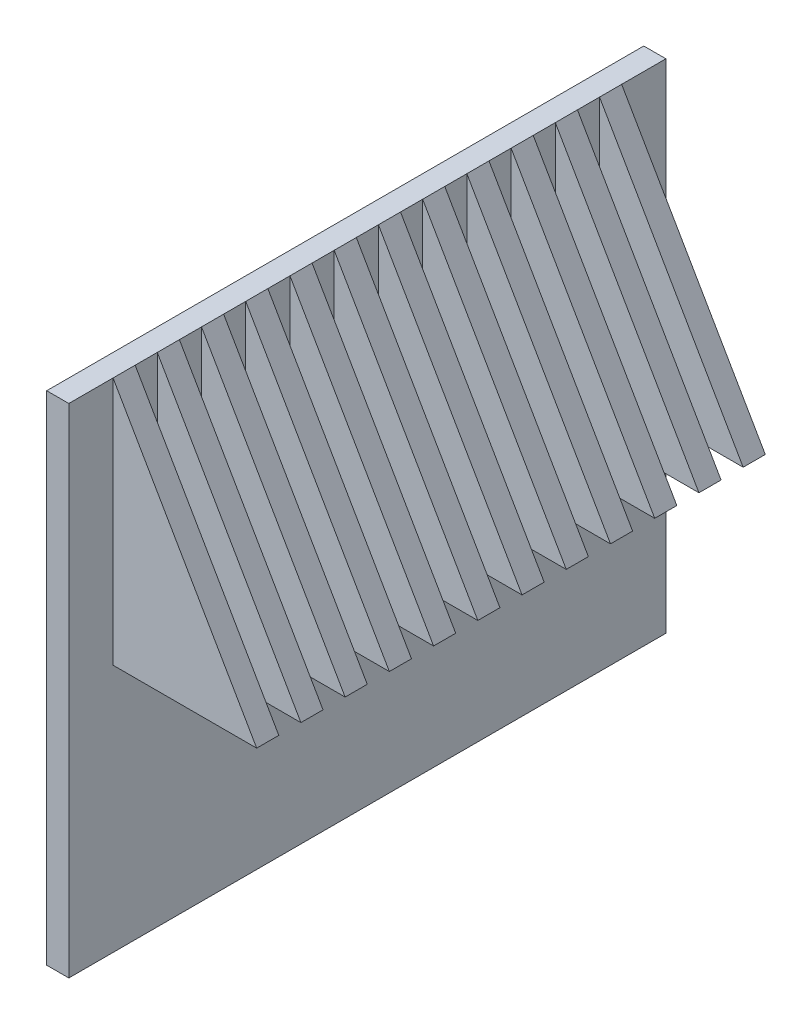
SolidWorks part; units mm, degrees
material "A286 Iron Base Superalloy"
ref_plane "Front Plane" through (0, 0, 0) normal (0, 0, 1) x (1, 0, 0)
ref_plane "Top Plane" through (0, 0, 0) normal (0, 1, 0) x (1, 0, 0)
ref_plane "Right Plane" through (0, 0, 0) normal (1, 0, 0) x (0, 0, -1)
sketch "Sketch2" plane through (0, 0, 0) normal (1, 0, 0) x (0, 0, -1)
  line L1 (0, 0) -> (270, 0)
  line L2 (0, 0) -> (0, 225)
  line L3 (0, 225) -> (270, 225)
  line L4 (270, 0) -> (270, 225)
  dimension "D1" = 270
  dimension "D2" = 225
extrude "Boss-Extrude1" add sketch "Sketch2" along normal blind 10
sketch "Sketch4" plane through (0, 0, 0) normal (0, 0, 1) x (1, 0, 0)
  line L0 (10, 225) -> (74.9519, 112.5)
  line L1 (10, 225) -> (10, 0) construction
  line L2 (10, 225) -> (10, 112.5)
  line L3 (10, 112.5) -> (74.9519, 112.5)
  dimension "D1" = 30
  dimension "D2" = 112.5
extrude "Boss-Extrude4" add sketch "Sketch4" against normal up to vertex (270 mm away) up to point (10, 225, -270)
sketch "Sketch5" plane through (0, 112.5, 0) normal (0, -1, 0) x (1, 0, 0)
  line L0 (10, -270) -> (10, -260)
  line L1 (10, -270) -> (10, 0) construction
  line L2 (10, -260) -> (74.9519, -260)
  line L3 (74.9519, -270) -> (74.9519, 0) construction
  line L4 (10, -250) -> (74.9519, -250)
  line L5 (10, -240) -> (74.9519, -240)
  line L6 (10, -230) -> (74.9519, -230)
  line L7 (10, -220) -> (74.9519, -220)
  line L8 (10, -260) -> (74.9519, -260)
  line L9 (10, -260) -> (10, -270)
  line L10 (10, -270) -> (74.9519, -270)
  line L11 (74.9519, -260) -> (74.9519, -270)
  line L12 (10, -210) -> (74.9519, -210)
  line L13 (10, -200) -> (74.9519, -200)
  line L14 (10, -190) -> (74.9519, -190)
  line L15 (10, -180) -> (74.9519, -180)
  line L16 (10, -170) -> (74.9519, -170)
  line L17 (10, -160) -> (74.9519, -160)
  line L18 (10, -150) -> (74.9519, -150)
  line L19 (10, -140) -> (74.9519, -140)
  line L20 (10, -130) -> (74.9519, -130)
  line L21 (10, -120) -> (74.9519, -120)
  line L22 (10, -110) -> (74.9519, -110)
  line L23 (10, -100) -> (74.9519, -100)
  line L24 (10, -90) -> (74.9519, -90)
  line L25 (10, -80) -> (74.9519, -80)
  line L26 (10, -70) -> (74.9519, -70)
  line L27 (10, -60) -> (74.9519, -60)
  line L28 (10, -50) -> (74.9519, -50)
  line L29 (10, -40) -> (74.9519, -40)
  line L30 (10, -30) -> (74.9519, -30)
  line L31 (10, -20) -> (74.9519, -20)
  line L32 (10, -10) -> (74.9519, -10)
  line L33 (10, 0) -> (74.9519, 0)
  line M2 (74.9519, 0) -> (10, 0)
  line M3 (10, 0) -> (10, -270)
  line M4 (10, -270) -> (74.9519, -270)
  line M5 (74.9519, -270) -> (74.9519, 0)
  dimension "D1" = 10
  dimension "D3" = 20
  dimension "D2" = 27
extrude "Cut-Extrude1" cut sketch "Sketch5" against normal through all contours L2 M3 M4 M5 | L4 L2 M3 M5 | L6 L5 M3 M5 | L12 L7 M3 M5 | L14 L13 M3 M5 | L16 L15 M3 M5 | L18 L17 M3 M5 | L20 L19 M3 M5 | L22 L21 M3 M5 | L24 L23 M3 M5 | L26 L25 M3 M5 | L28 L27 M3 M5 | L30 L29 M3 M5 | L32 L31 M3 M5 | L32 M3 M5 M2
